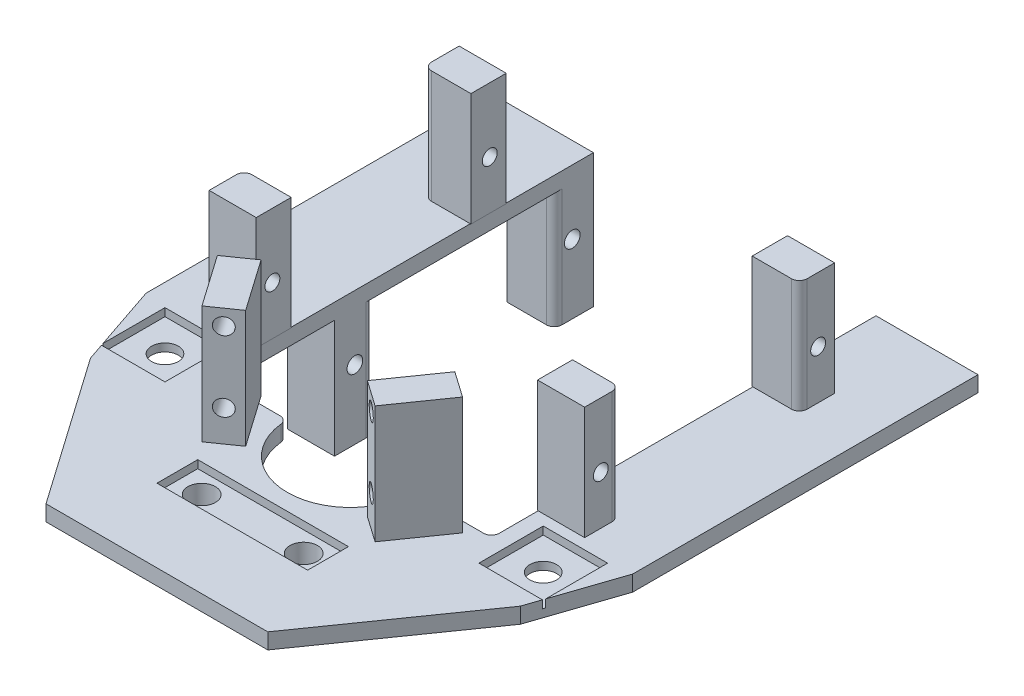
SolidWorks part; units mm, degrees
ref_plane "前视基准面" through (0, 0, 0) normal (0, 0, 1) x (1, 0, 0)
ref_plane "上视基准面" through (0, 0, 0) normal (0, 1, 0) x (1, 0, 0)
ref_plane "右视基准面" through (0, 0, 0) normal (1, 0, 0) x (0, 0, -1)
other "Configuration Table"
sketch "草图1" plane through (0, 0, 0) normal (0, 1, 0) x (1, 0, 0)
  line L0 (5, 0) -> (31, 0)
  line L1 (-5, 0) -> (-31, 0)
  line L2 (-31, 0) -> (-31, -12.2661)
  line L3 (-17.5617, -40) -> (17.5617, -40)
  line L4 (31, -12.2661) -> (31, 0)
  line L6 (5, 0) -> (5, -5)
  line L8 (-5, -5) -> (-5, 0)
  line L9 (-31, -12.2661) -> (-17.5617, -40)
  line L10 (0, -55) -> (0, 55) construction
  line L11 (31, -12.2661) -> (17.5617, -40)
  arc A0 (-5, -5) -> (5, -5) centre (0, -5) ccw
  point P9 (0, 0)
  dimension "D5" = 5
extrude "凸台-拉伸1" add sketch "草图1" along normal blind 2
sketch "草图2" plane through (0, 0, 0) normal (0, -1, 0) x (1, 0, 0)
  line L0 (-31, 0) -> (-24.3706, 19.6082)
  line L1 (-24.3706, 19.6082) -> (-13.0133, 35.516)
  line L2 (-13.0133, 35.516) -> (-4.4102, 40)
  line L3 (-17.5617, 40) -> (17.5617, 40) construction
  line L4 (-4.4102, 40) -> (-17.5617, 40)
  line L5 (-17.5617, 40) -> (-31, 12.2661)
  line L6 (-31, 12.2661) -> (-31, 0)
  spline S0 degree 3 poles (-24.6749, 18.9124) (-24.6476, 18.978) (-24.5919, 19.1091) (-24.506, 19.3054) (-24.4186, 19.5018) (-24.3006, 19.7642) (-24.21, 19.96) (-24.0859, 20.2179) (-24.0222, 20.3453) (-23.9266, 20.5353) (-23.8947, 20.5985) (-23.8313, 20.7248) (-23.7682, 20.851) (-23.6734, 21.0397) (-23.6095, 21.1647) (-23.5771, 21.227) knots 312 312 312 312 313.000001 314.000001 315 316.000001 318 318.000001 320.000001 320.000001 321 321.000001 322.000001 323.000001 324 324 324 324 construction
  spline S1 degree 3 poles (-13.0133, 35.516) (-13.0693, 35.4858) (-13.2423, 35.4027) (-13.419, 35.3306) (-13.5292, 35.2769) knots 87 87 87 87 88.000001 90 90 90 90 construction
  spline S2 degree 3 poles (-12.4383, 35.1007) (-12.5045, 35.1532) (-12.6106, 35.2289) (-12.8359, 35.3844) (-12.9548, 35.4707) (-13.0133, 35.516) knots 0 0 0 0 1 2 3 3 3 3 construction
extrude "切除-拉伸1" cut sketch "草图2" against normal blind 2
mirror "镜向1" about plane through (0, 0, 0) normal (1, 0, 0) of "切除-拉伸1"
sketch "草图3" plane through (0, 2, 0) normal (0, 1, 0) x (1, 0, 0)
  line L0 (1.7645, -32.1877) -> (-1.2355, -32.1877)
  line L2 (-1.2355, -29.1877) -> (1.7645, -29.1877)
  line L6 (-1.2355, -29.1877) -> (-1.2355, -32.1877)
  line L8 (1.7645, -29.1877) -> (1.7645, -32.1877)
sketch "草图4" plane through (0, 2, 0) normal (0, 1, 0) x (1, 0, 0)
  line L3 (12.4653, -10.8088) -> (14.186, -8.3513)
  line L13 (12.4653, -10.8088) -> (11.0314, -12.8566)
  line L15 (10.9094, -6.057) -> (9.1887, -8.5145)
  line L16 (11.0314, -12.8566) -> (7.7547, -10.5623)
  line L17 (7.7547, -10.5623) -> (9.1887, -8.5145)
  line L18 (10.9094, -6.057) -> (12.3434, -4.0091)
  line L19 (12.3434, -4.0091) -> (15.62, -6.3034)
  line L20 (15.62, -6.3034) -> (14.186, -8.3513)
  dimension "D1" = 4
  dimension "D2" = 2.5
  dimension "D3" = 2.5
extrude "凸台-拉伸2" add sketch "草图3" along normal blind 12
extrude "凸台-拉伸3" add sketch "草图4" along normal blind 15
sketch "草图5" plane through (-1.2355, 0, 0) normal (-1, 0, 0) x (0, 0, 1)
  line L0 (32.1877, 2) -> (32.1877, 4.5) construction
  line L2 (32.1877, 4.5) -> (30.6877, 4.5) construction
  line L3 (30.6877, 4.5) -> (30.6877, 11.5) construction
  circle A0 centre (30.6877, 11.5) radius 0.75
  circle A1 centre (30.6877, 4.5) radius 0.75
  dimension "D4" = 1.5
  dimension "D5" = 1.5
  dimension "D1" = 2.5
  dimension "D2" = 1.5
  dimension "D3" = 7
extrude "切除-拉伸2" cut sketch "草图5" against normal blind 12
sketch "草图6" plane through (25.9389, 0, 23.295) normal (-0.5736, 0, 0.8192) x (0.8192, 0, 0.5736)
  line L0 (-24.898, 2) -> (-15.2789, 2) construction
  line L3 (-22.1987, 17) -> (-18.1987, 17) construction
  line L5 (-22.1987, 17) -> (-18.1987, 17)
  circle A0 centre (-20.1987, 15) radius 1.05
  circle A1 centre (-20.1987, 6) radius 1.05
  point P11 (-20.1987, 17)
  dimension "D4" = 2.1
  dimension "D5" = 2.1
  dimension "D1" = 4
  dimension "D3" = 9
extrude "切除-拉伸3" cut sketch "草图6" against normal blind 12 contours A0 | A1
mirror "镜向2" about plane through (0, 0, 0) normal (1, 0, 0) of "凸台-拉伸3", "切除-拉伸3"
sketch "草图7" plane through (0, 2, 0) normal (0, 1, 0) x (1, 0, 0)
  line L0 (-31, 0) -> (-31, 60)
  line L1 (-5, 0) -> (-5, 60)
  line L2 (-5, 60) -> (-31, 60)
  line L3 (-31, 0) -> (-5, 0)
  line L7 (5, 0) -> (31, 0)
  line L11 (5, 0) -> (5, 60)
  line L12 (5, 60) -> (31, 60)
  line L13 (31, 60) -> (31, 0)
  dimension "D1" = 60
extrude "凸台-拉伸4" add sketch "草图7" against normal blind 2
sketch "草图8" plane through (0, 2, 0) normal (0, 1, 0) x (1, 0, 0)
  line L2 (23.9234, 5.4086) -> (17.9234, 5.4086)
  line L5 (17.9234, 5.4086) -> (17.9234, 0.9514)
  line L12 (23.9234, 5.4086) -> (23.9234, 0.9514)
  line L13 (23.9234, 0.9514) -> (17.9234, 0.9514)
  line L15 (17.9234, 28.3086) -> (17.9234, 32.8086)
  line L17 (17.9234, 32.8086) -> (23.9234, 32.8086)
  line L18 (23.9234, 32.8086) -> (23.9234, 28.3086)
  line L19 (23.9234, 28.3086) -> (17.9234, 28.3086)
  dimension "D1" = 6
  dimension "D2" = 6
extrude "凸台-拉伸5" add sketch "草图8" along normal blind 14.4
sketch "草图9" plane through (31, 0, 0) normal (1, 0, 0) x (0, 0, -1)
  line L0 (5.4086, 2) -> (3.0086, 2) construction
  line L1 (3.0086, 2) -> (3.0086, 8.2) construction
  line L2 (3.0086, 8.2) -> (30.7086, 8.2) construction
  circle A0 centre (3.0086, 8.2) radius 0.95
  circle A1 centre (30.7086, 8.2) radius 0.95
  dimension "D3" = 1.9
  dimension "D5" = 1.9
  dimension "D1" = 2.4
  dimension "D2" = 6.2
  dimension "D4" = 27.7
extrude "切除-拉伸4" cut sketch "草图9" against normal blind 14.4
mirror "镜向3" about plane through (0, 0, 0) normal (1, 0, 0) of "切除-拉伸4", "凸台-拉伸5"
sketch "草图10" plane through (0, 2, 0) normal (0, 1, 0) x (1, 0, 0)
  line L0 (-31, 60) -> (-31, 68)
  line L1 (-31, 68) -> (-5, 68)
  line L2 (-5, 68) -> (-5, 60)
  line L3 (5, 60) -> (5, 68)
  line L4 (5, 68) -> (30.7986, 68)
  line L5 (30.7986, 68) -> (31, 60)
  line L6 (-31, 60) -> (-5, 60)
  line L7 (5, 60) -> (31, 60)
  dimension "D1" = 8
extrude "凸台-拉伸6" add sketch "草图10" against normal up to surface (2 mm away) up to face at (0, 0, -2.4823)
sketch "草图11" plane through (0, 2, 0) normal (0, 1, 0) x (1, 0, 0)
  line L0 (17.9234, 32.8086) -> (17.9234, 34.8086) construction
  line L1 (0, 34.8086) -> (16.28, 34.8086) construction
  line L2 (16.28, 34.8086) -> (16.28, 39.3086)
  line L3 (16.28, 39.3086) -> (20.78, 39.3086)
  line L4 (20.78, 39.3086) -> (20.78, 34.8086)
  line L5 (20.78, 34.8086) -> (16.28, 34.8086)
  line L6 (16.28, 39.3086) -> (16.28, 62.2086) construction
  line L7 (16.28, 62.2086) -> (20.78, 62.2086)
  line L8 (20.78, 62.2086) -> (20.78, 66.7086)
  line L9 (20.78, 66.7086) -> (16.28, 66.7086)
  line L10 (16.28, 66.7086) -> (16.28, 62.2086)
  dimension "D4" = 4.5
  dimension "D1" = 2
  dimension "D2" = 16.28
  dimension "D3" = 4.5
  dimension "D5" = 22.9
  dimension "D6" = 4.5
  dimension "D7" = 4.5
extrude "凸台-拉伸7" add sketch "草图11" along normal blind 14.4
sketch "草图12" plane through (16.28, 0, 0) normal (-1, 0, 0) x (0, 0, 1)
  line L0 (-39.3086, 2) -> (-39.3086, 8.2) construction
  line L1 (-39.3086, 16.4) -> (-39.3086, 2) construction
  line L2 (-39.3086, 8.2) -> (-36.9086, 8.2) construction
  line L3 (-62.2086, 2) -> (-62.2086, 8.2) construction
  line L4 (-62.2086, 16.4) -> (-62.2086, 2) construction
  line L5 (-62.2086, 8.2) -> (-64.6086, 8.2) construction
  circle A1 centre (-36.9086, 8.2) radius 0.95
  circle A2 centre (-64.6086, 8.2) radius 0.95
  dimension "D3" = 1.9
  dimension "D5" = 1.9
  dimension "D1" = 6.2
  dimension "D2" = 2.4
  dimension "D4" = 2.4
extrude "切除-拉伸5" cut sketch "草图12" against normal blind 14.4
sketch "草图13" plane through (0, 16.4, 0) normal (0, 1, 0) x (1, 0, 0)
  line L0 (20.78, 34.8086) -> (16.28, 34.8086)
  line L1 (16.28, 34.8086) -> (16.28, 39.3086)
  line L2 (16.28, 39.3086) -> (20.78, 39.3086)
  line L3 (20.78, 39.3086) -> (20.78, 34.8086)
  line L4 (20.78, 66.7086) -> (16.28, 66.7086)
  line L5 (16.28, 66.7086) -> (16.28, 62.2086)
  line L6 (16.28, 62.2086) -> (20.78, 62.2086)
  line L7 (20.78, 62.2086) -> (20.78, 66.7086)
  dimension "D1" = 4.5
  dimension "D2" = 4.5
extrude "切除-拉伸6" cut sketch "草图13" against normal blind 14.4
sketch "草图14" plane through (0, 14, 0) normal (0, 1, 0) x (1, 0, 0)
  line L0 (-1.2355, -29.1877) -> (-1.2355, -32.1877)
  line L1 (-1.2355, -32.1877) -> (1.7645, -32.1877)
  line L2 (1.7645, -32.1877) -> (1.7645, -29.1877)
  line L3 (1.7645, -29.1877) -> (-1.2355, -29.1877)
sketch "草图15" plane through (0, 2, 0) normal (0, 1, 0) x (1, 0, 0)
  circle A0 centre (-6.2355, -17.6877) radius 1.75
  circle A1 centre (6.7645, -17.6877) radius 1.75
  dimension "D3" = 3.5
  dimension "D4" = 3.5
extrude "切除-拉伸8" cut sketch "草图15" against normal blind 12
extrude "切除-拉伸9" cut sketch "草图14" against normal blind 12
sketch "草图17" plane through (0, 0, 0) normal (0, -1, 0) x (1, 0, 0)
  line L0 (-20.5334, -44) -> (-31, -44)
  line L1 (-31, -68) -> (-31, 0) construction
  line L3 (-31, -68) -> (30.7986, -68)
  line L5 (31, 0) -> (31, -60) construction
  line L6 (31, -44) -> (-20.5334, -44)
  line L7 (-31, -44) -> (-37, -44)
  line L8 (-37, -44) -> (-37, -68)
  line L9 (-37, -68) -> (-31, -68)
  line L10 (30.7986, -68) -> (38, -68)
  line L11 (38, -68) -> (38, -44)
  line L12 (38, -44) -> (31, -44)
  dimension "D1" = 24
  dimension "D2" = 75
  dimension "D3" = 6
extrude "切除-拉伸11" cut sketch "草图17" against normal blind 10
sketch "草图20" plane through (0, 0, 0) normal (0, -1, 0) x (1, 0, 0)
  line L0 (5, -44) -> (8, -44)
  line L1 (31, -44) -> (5, -44) construction
  line L2 (8, -44) -> (8, 5)
  line L5 (-8, 5) -> (-8, -44)
  line L7 (-8, -44) -> (5, -44)
  arc A0 (8, 5) -> (-8, 5) centre (0, 5) ccw
  dimension "D1" = 8
  dimension "D2" = 5
extrude "切除-拉伸13" cut sketch "草图20" against normal mid plane 10
sketch "草图22" plane through (0, 2, 0) normal (0, 1, 0) x (1, 0, 0)
  line L6 (20, -0.399) -> (28.2, -0.399)
  line L7 (28.2, -0.399) -> (28.2, -8.599)
  line L8 (28.2, -8.599) -> (20, -8.599)
  line L9 (20, -8.599) -> (20, -0.399)
  line L10 (0, -16.94) -> (0, 16.94) construction
  line L11 (-28.2, -8.599) -> (-20, -8.599)
  line L12 (-28.2, -0.399) -> (-28.2, -8.599)
  line L13 (-20, -0.399) -> (-28.2, -0.399)
  line L14 (-20, -8.599) -> (-20, -0.399)
  dimension "D1" = 40
  dimension "D2" = 20
  dimension "D3" = 8.2
  dimension "D4" = 8.2
  dimension "D5" = 20
extrude "切除-拉伸15" cut sketch "草图22" against normal blind 1
sketch "草图23" plane through (0, 2, 0) normal (0, 1, 0) x (1, 0, 0)
  line L0 (8, -5) -> (18, -5)
  line L1 (18, -5) -> (18, 44)
  line L3 (18, 44) -> (8, 44)
  line L4 (8, 44) -> (8, -5)
  dimension "D1" = 10
extrude "切除-拉伸16" cut sketch "草图23" against normal blind 10
mirror "镜向6" about plane through (0, 0, 0) normal (1, 0, 0) of "切除-拉伸16"
fillet "圆角4" radius 1 4 edges at (18, 1, 5) (8, 1, 5) (-18, 1, 5) (-8, 1, 5)
sketch "草图24" plane through (0, 2, 0) normal (0, 1, 0) x (1, 0, 0)
  line L0 (0.2645, -20.1876) -> (0.2645, -15.1877) construction
  line L3 (9.8645, -15.0876) -> (-9.3355, -15.0876)
  line L4 (9.8645, -15.0876) -> (9.8645, -20.2876)
  line L5 (9.8645, -20.2876) -> (-9.3355, -20.2876)
  line L6 (-9.3355, -15.0876) -> (-9.3355, -20.2876)
  line L7 (9.8645, -15.0876) -> (-9.3355, -20.2876) construction
  line L8 (9.8645, -20.2876) -> (-9.3355, -15.0876) construction
  point P4 (0.2645, -17.6876)
  dimension "D1" = 5.2
  dimension "D2" = 19.2
extrude "切除-拉伸17" cut sketch "草图24" against normal blind 1
sketch "草图25" plane through (0, 1, 0) normal (0, 1, 0) x (1, 0, 0)
  line L0 (0.2645, -15.0876) -> (0.2645, -20.2876) construction
  line L1 (9.8645, -15.0876) -> (-9.3355, -15.0876) construction
  line L2 (-9.3355, -20.2876) -> (9.8645, -20.2876) construction
  line L4 (-10.3355, -14.0876) -> (10.8645, -14.0876)
  line L5 (-10.3355, -14.0876) -> (-10.3355, -21.2876)
  line L6 (-10.3355, -21.2876) -> (10.8645, -21.2876)
  line L7 (10.8645, -14.0876) -> (10.8645, -21.2876)
  line L8 (-10.3355, -14.0876) -> (10.8645, -21.2876) construction
  line L9 (-10.3355, -21.2876) -> (10.8645, -14.0876) construction
  circle A1 centre (-6.2355, -17.6877) radius 1.75
  circle A2 centre (6.7645, -17.6877) radius 1.75
  point P6 (0.2645, -17.6876)
  dimension "D1" = 7.2
  dimension "D2" = 21.2
extrude "凸台-拉伸10" add sketch "草图25" against normal blind 2 from offset 1 offset against normal yes
fillet "圆角5" radius 1 4 edges at (10.8645, -1, 14.0876) (-10.3355, -1, 14.0876) (-10.3355, -1, 21.2876) (10.8645, -1, 21.2876)
sketch "草图26" plane through (0, 2, 0) normal (0, 1, 0) x (1, 0, 0)
  line L2 (-35.0065, 0) -> (-35.0065, -42.039)
  line L3 (-35.0065, -42.039) -> (35.0065, -42.039)
  line L4 (35.0065, 0) -> (35.0065, -42.039)
  line L6 (-35.0065, -42.039) -> (0, 0) construction
  line L7 (0, 0) -> (35.0065, -42.039) construction
  arc A1 (-35.0065, 0) -> (35.0065, 0) centre (0, 0) ccw
extrude "切除-拉伸18" cut sketch "草图26" against normal blind 10
sketch "草图27" plane through (0, 2, 0) normal (0, 1, 0) x (1, 0, 0)
  line L0 (-27.3798, -10.7077) -> (-14.1312, -29.6287)
  line L1 (-31, 0) -> (-28.2, -8.2818) construction
  line L2 (-14.1312, -29.6287) -> (-14.1312, -32.0275)
  line L3 (-14.1312, -32.0275) -> (-27.3798, -32.0275)
  line L4 (-27.3798, -32.0275) -> (-27.3798, -10.7077)
  line L5 (-11.0314, -12.8566) -> (-15.62, -6.3034) construction
  arc A0 (-16.2228, -31.0205) -> (16.2228, -31.0205) centre (0, 0) ccw construction
extrude "切除-拉伸19" cut sketch "草图27" against normal blind 10
mirror "镜向4" about plane through (0, 0, 0) normal (1, 0, 0) of "切除-拉伸19"
fillet "圆角7" radius 1 4 edges at (-23.9234, 9.2, -5.4086) (23.9234, 9.2, -5.4086) (23.9234, 9.2, -28.3086) (-23.9234, 9.2, -28.3086)
ref_plane "基准面1" through (-24, 0, 0) normal (-1, 0, 0) x (0, 0, 1)
sketch "草图33" plane through (-24, 0, 0) normal (-1, 0, 0) x (0, 0, 1)
  line L0 (-44, 0) -> (0, 0) construction
  line L2 (-44, 0) -> (-44, -15)
  line L3 (-44, -15) -> (-39, -15)
  line L4 (-39, 0) -> (-39, -15)
  line L5 (-44, 0) -> (-44, 2) construction
  line L7 (-16, 0) -> (-16, -15)
  line L8 (-16, -15) -> (-11, -15)
  line L9 (-11, 0) -> (-11, -15)
  line L10 (-44, 2) -> (0, 2) construction
  line L12 (-44, 0) -> (-44, 2)
  line L13 (-44, 2) -> (-39, 2)
  line L14 (-39, 0) -> (-39, 2)
  line L16 (-16, 0) -> (-16, 2)
  line L17 (-16, 2) -> (-11, 2)
  line L18 (-11, 0) -> (-11, 2)
  dimension "D1" = 23
  dimension "D2" = 5
  dimension "D3" = 15
extrude "凸台-拉伸12" add sketch "草图33" against normal blind 6
sketch "草图34" plane through (-18, 0, 0) normal (1, 0, 0) x (0, 0, -1)
  line L0 (0, 0) -> (44, 0) construction
  line L1 (16, 0) -> (16, -15) construction
  circle A0 centre (13.6, -6.2) radius 1
  circle A1 centre (41.3, -6.2) radius 1
  dimension "D1" = 2
  dimension "D2" = 6.2
  dimension "D3" = 2.4
  dimension "D4" = 27.7
extrude "切除-拉伸24" cut sketch "草图34" against normal blind 10
fillet "圆角9" radius 1 2 edges at (-18, -7.5, -16) (-18, -7.5, -39)
sketch "草图31" plane through (0, 2, 0) normal (0, 1, 0) x (1, 0, 0)
  line L1 (-14.1312, -29.6287) -> (14.1312, -29.6287)
  line L2 (-14.1312, -29.6287) -> (-14.1312, -35.0065)
  line L3 (-14.1312, -35.0065) -> (14.1312, -35.0065)
  line L4 (14.1312, -29.6287) -> (14.1312, -35.0065)
  line L5 (14.1312, -32.0275) -> (14.1312, -29.6287) construction
  arc A0 (-14.1312, -32.0275) -> (14.1312, -32.0275) centre (0, 0) ccw construction
extrude "切除-拉伸22" cut sketch "草图31" against normal blind 10
sketch "草图32" plane through (0, 1, 0) normal (0, 1, 0) x (1, 0, 0)
  line L0 (-20, -8.599) -> (-20, -0.399) construction
  line L1 (-20, -0.399) -> (-28.2, -0.399) construction
  line L2 (28.2, -0.399) -> (20, -0.399) construction
  circle A0 centre (-24.1, -4.499) radius 1.7
  circle A1 centre (24.1, -4.499) radius 1.7
  point P8 (-20, -4.499)
  point P12 (-24.1, -0.399)
  point P15 (24.1, -0.399)
  dimension "D1" = 3.4
extrude "切除-拉伸23" cut sketch "草图32" against normal blind 10
